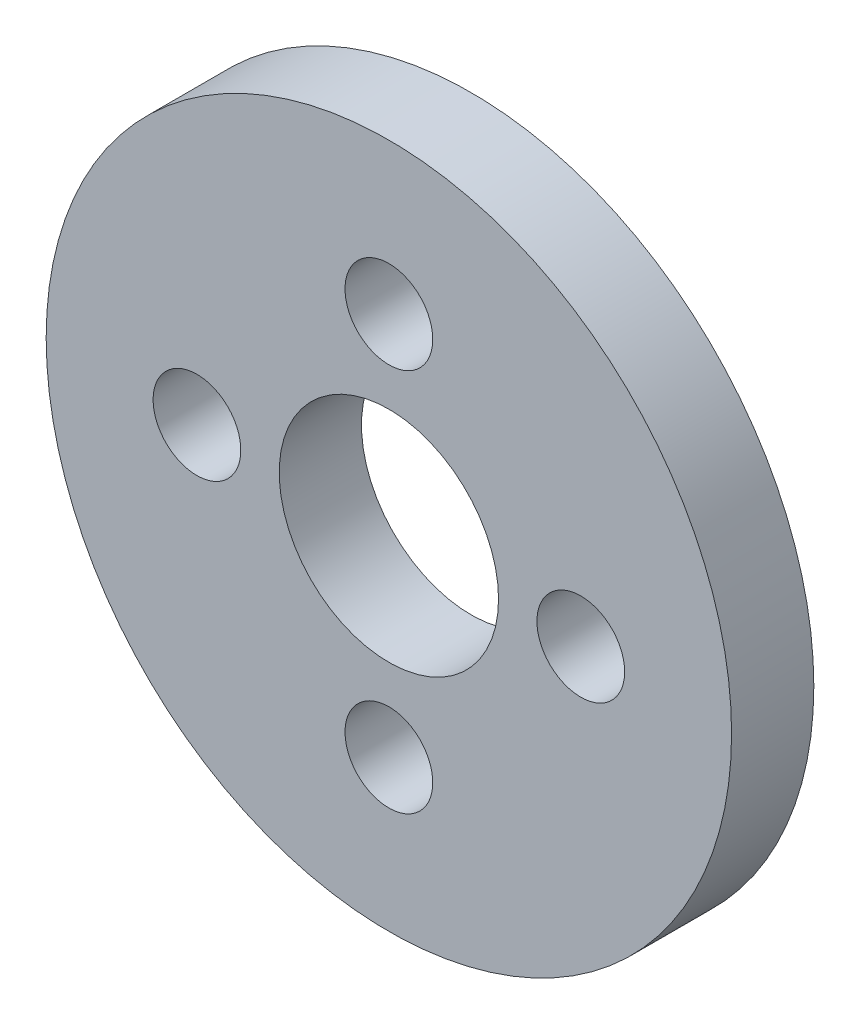
SolidWorks part; units mm, degrees
ref_plane "前视基准面" through (0, 0, 0) normal (0, 0, 1) x (1, 0, 0)
ref_plane "上视基准面" through (0, 0, 0) normal (0, 1, 0) x (1, 0, 0)
ref_plane "右视基准面" through (0, 0, 0) normal (1, 0, 0) x (0, 0, -1)
sketch "草图1" plane through (0, 0, 0) normal (0, 0, 1) x (1, 0, 0)
  line L0 (0, 7) -> (0, -7) construction
  line L1 (7, 0) -> (-7, 0) construction
  circle A0 centre (0, 0) radius 10 construction
  circle A1 centre (0, 0) radius 7 construction
  circle A2 centre (0, 0) radius 4
  circle A3 centre (0, 0) radius 12.5
  circle A4 centre (0, 7) radius 1.6
  circle A5 centre (7, 0) radius 1.6
  circle A6 centre (-7, 0) radius 1.6
  circle A7 centre (0, -7) radius 1.6
  point P17 (0.001, 0)
  dimension "D1" = 7
  dimension "D2" = 20
  dimension "D3" = 25
  dimension "D5" = 8
extrude "凸台-拉伸1" add sketch "草图1" along normal blind 3
